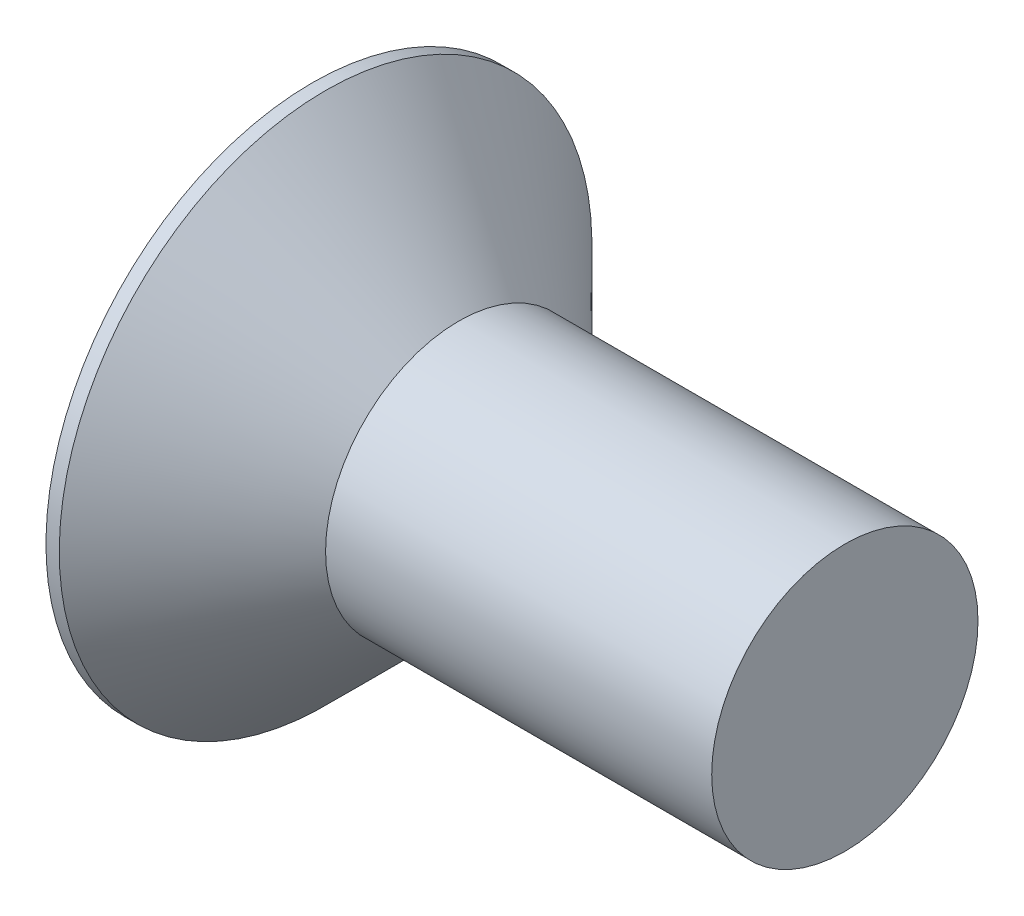
SolidWorks part; units mm, degrees
material "Plain Carbon Steel"
ref_plane "Front Plane" through (0, 0, 0) normal (0, 0, 1) x (1, 0, 0)
ref_plane "Top Plane" through (0, 0, 0) normal (0, 1, 0) x (1, 0, 0)
ref_plane "Right Plane" through (0, 0, 0) normal (1, 0, 0) x (0, 0, -1)
sketch "Sketch1" plane through (0, 0, 0) normal (0, 0, 1) x (1, 0, 0)
  line L0 (0, 0) -> (0, 6)
  line L1 (0, 6) -> (0.3, 6)
  line L2 (0.3, 6) -> (3.3, 3)
  line L3 (3.3, 3) -> (12, 3)
  line L4 (12, 3) -> (12, 0)
  line L5 (12, 0) -> (0, 0) construction
  line L6 (0, 0) -> (12, 0)
  dimension "D1" = 45
  dimension "D2" = 6
  dimension "D3" = 12
  dimension "D4" = 3.3
  dimension "D5" = 12
revolve "Revolve1" add sketch "Sketch1" angle 360 about L5
sketch "Sketch2" plane through (0, 0, 0) normal (-1, 0, 0) x (0, 0, 1)
  line L1 (1.1547, 2) -> (-1.1547, 2)
  line L2 (-1.1547, 2) -> (-2.3094, 0)
  line L3 (-2.3094, 0) -> (-1.1547, -2)
  line L4 (-1.1547, -2) -> (1.1547, -2)
  line L5 (1.1547, -2) -> (2.3094, 0)
  line L6 (2.3094, 0) -> (1.1547, 2)
  circle A1 centre (0, 0) radius 2 construction
  dimension "D1" = 4
extrude "Cut-Extrude1" cut sketch "Sketch2" against normal blind 2
